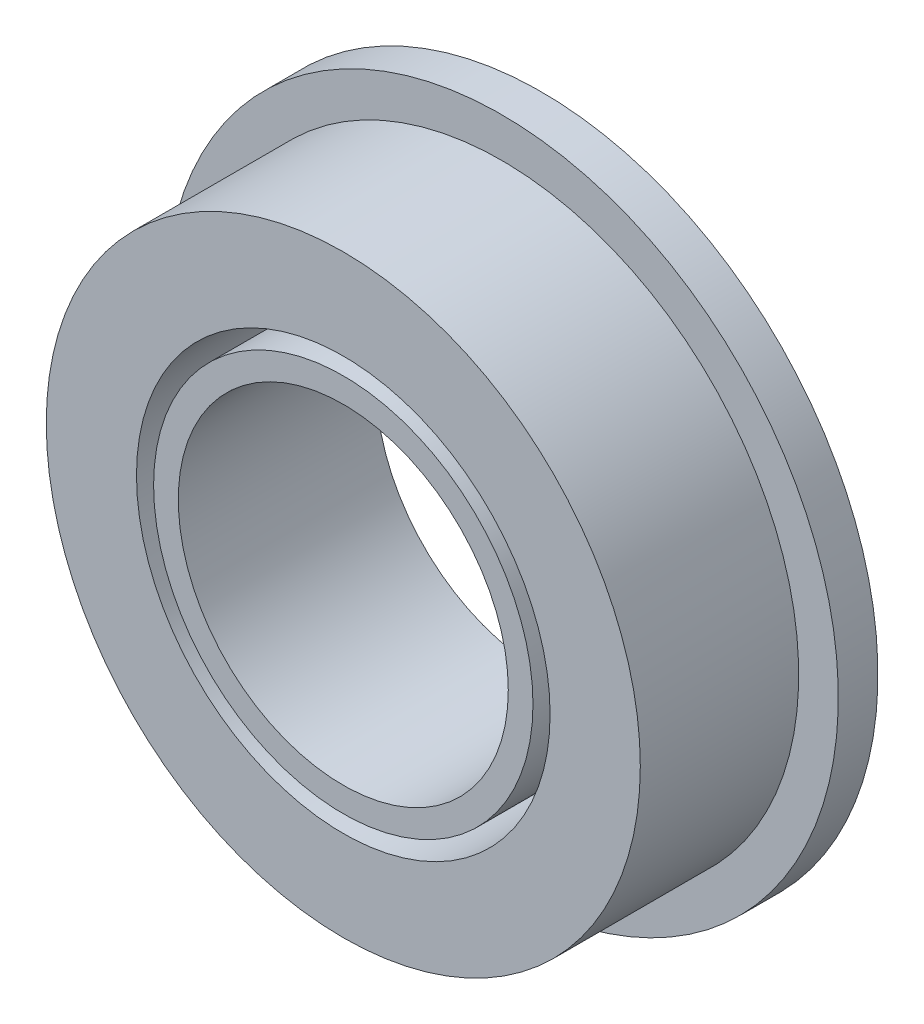
SolidWorks part; units mm, degrees
material "6061 Alloy"
ref_plane "Front Plane" through (0, 0, 0) normal (0, 0, 1) x (1, 0, 0)
ref_plane "Top Plane" through (0, 0, 0) normal (0, 1, 0) x (1, 0, 0)
ref_plane "Right Plane" through (0, 0, 0) normal (1, 0, 0) x (0, 0, -1)
other "Configuration Table"
sketch "Sketch1" plane through (0, 0, 0) normal (0, 0, 1) x (1, 0, 0)
  circle A0 centre (0, 0) radius 4.5
  circle A1 centre (0, 0) radius 2.5
  dimension "D1" = 9
  dimension "D2" = 5
extrude "Boss-Extrude1" add sketch "Sketch1" along normal blind 3
sketch "Sketch2" plane through (0, 0, 0) normal (0, 0, -1) x (-1, 0, 0)
  circle A0 centre (0, 0) radius 5.1
  circle A1 centre (0, 0) radius 2.5 construction
  circle A2 centre (0, 0) radius 2.5
  dimension "D1" = 10.2
extrude "Boss-Extrude2" add sketch "Sketch2" against normal blind 0.6
sketch "Sketch3" plane through (0, 0, 0) normal (0, 0, -1) x (-1, 0, 0)
  circle A0 centre (0, 0) radius 2.874
  circle A1 centre (0, 0) radius 3.1332
extrude "Cut-Extrude1" cut sketch "Sketch3" against normal blind 6.6
